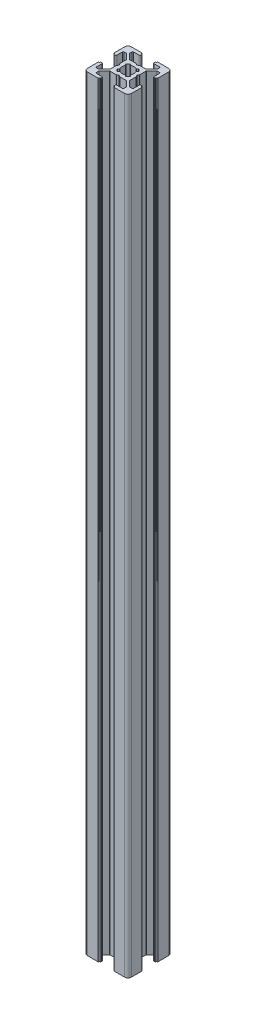
SolidWorks part; units mm, degrees
material "6061 Alloy"
ref_plane "Front Plane" through (0, 0, 0) normal (0, 0, 1) x (1, 0, 0)
ref_plane "Top Plane" through (0, 0, 0) normal (0, 1, 0) x (1, 0, 0)
ref_plane "Right Plane" through (0, 0, 0) normal (1, 0, 0) x (0, 0, -1)
sketch "Sketch2" plane through (0, 0, 0) normal (0, 1, 0) x (1, 0, 0)
  line L0 (-10, 3.75) -> (-10, 8.5)
  line L1 (10, -10) -> (-10, -10) construction
  line L2 (10, -10) -> (10, 10) construction
  line L3 (10, 10) -> (-10, 10) construction
  line L4 (-10, -10) -> (-10, 10) construction
  line L5 (10, -10) -> (-10, 10) construction
  line L6 (10, 10) -> (-10, -10) construction
  line L7 (-9.8, 3.55) -> (-9.7, 3.55)
  line L8 (-9.5, 3.35) -> (-9.5, 3.2)
  line L9 (-9.3, 3) -> (-8.9, 3)
  line L10 (-8.5, 3.4) -> (-8.5, 5.9)
  line L11 (-8.1, 6.3) -> (-7.1728, 6.3)
  line L12 (-6.8899, 6.1828) -> (-4.6172, 3.9101)
  line L13 (-4.5, 3.6272) -> (-4.5, 0.9196)
  line L14 (-4.4732, 0.8196) -> (-4.0577, 0.1)
  line L15 (-2.4797, 1.419) -> (-2.8968, 1.8361)
  line L16 (0, 0) -> (-10, 0) construction
  line L17 (-2.4797, -1.419) -> (-2.8968, -1.8361)
  line L18 (-4.4732, -0.8196) -> (-4.0577, -0.1)
  line L19 (-4.5, -3.6272) -> (-4.5, -0.9196)
  line L20 (-6.8899, -6.1828) -> (-4.6172, -3.9101)
  line L21 (-8.1, -6.3) -> (-7.1728, -6.3)
  line L22 (-8.5, -3.4) -> (-8.5, -5.9)
  line L23 (-9.3, -3) -> (-8.9, -3)
  line L24 (-9.5, -3.35) -> (-9.5, -3.2)
  line L25 (-9.8, -3.55) -> (-9.7, -3.55)
  line L26 (-10, -3.75) -> (-10, -8.5)
  line L27 (-6.3, 8.1) -> (-6.3, 7.1728)
  line L28 (1.419, 2.4797) -> (1.8361, 2.8968)
  line L29 (6.1828, 6.8899) -> (3.9101, 4.6172)
  line L30 (6.3, 8.1) -> (6.3, 7.1728)
  line L31 (3.75, 10) -> (8.5, 10)
  line L32 (3.55, 9.8) -> (3.55, 9.7)
  line L33 (3.35, 9.5) -> (3.2, 9.5)
  line L34 (3, 9.3) -> (3, 8.9)
  line L35 (3.4, 8.5) -> (5.9, 8.5)
  line L36 (3.6272, 4.5) -> (0.9196, 4.5)
  line L37 (0.8196, 4.4732) -> (0.1, 4.0577)
  line L38 (-0.8196, 4.4732) -> (-0.1, 4.0577)
  line L39 (-1.419, 2.4797) -> (-1.8361, 2.8968)
  line L40 (-3.6272, 4.5) -> (-0.9196, 4.5)
  line L41 (-6.1828, 6.8899) -> (-3.9101, 4.6172)
  line L42 (-3.4, 8.5) -> (-5.9, 8.5)
  line L43 (-3, 9.3) -> (-3, 8.9)
  line L44 (-3.35, 9.5) -> (-3.2, 9.5)
  line L45 (-3.55, 9.8) -> (-3.55, 9.7)
  line L46 (-3.75, 10) -> (-8.5, 10)
  line L47 (10, -3.75) -> (10, -8.5)
  line L48 (9.8, -3.55) -> (9.7, -3.55)
  line L49 (9.5, -3.35) -> (9.5, -3.2)
  line L50 (9.3, -3) -> (8.9, -3)
  line L51 (8.5, -3.4) -> (8.5, -5.9)
  line L52 (6.8899, -6.1828) -> (4.6172, -3.9101)
  line L53 (4.5, -3.6272) -> (4.5, -0.9196)
  line L54 (2.4797, -1.419) -> (2.8968, -1.8361)
  line L55 (4.4732, -0.8196) -> (4.0577, -0.1)
  line L56 (4.4732, 0.8196) -> (4.0577, 0.1)
  line L57 (4.5, 3.6272) -> (4.5, 0.9196)
  line L58 (8.5, 3.4) -> (8.5, 5.9)
  line L59 (9.3, 3) -> (8.9, 3)
  line L60 (9.5, 3.35) -> (9.5, 3.2)
  line L61 (9.8, 3.55) -> (9.7, 3.55)
  line L62 (10, 3.75) -> (10, 8.5)
  line L63 (8.1, 6.3) -> (7.1728, 6.3)
  line L64 (6.8899, 6.1828) -> (4.6172, 3.9101)
  line L65 (2.4797, 1.419) -> (2.8968, 1.8361)
  line L66 (8.1, -6.3) -> (7.1728, -6.3)
  line L67 (-3.75, -10) -> (-8.5, -10)
  line L68 (-3.55, -9.8) -> (-3.55, -9.7)
  line L69 (-3.35, -9.5) -> (-3.2, -9.5)
  line L70 (-3, -9.3) -> (-3, -8.9)
  line L71 (-3.4, -8.5) -> (-5.9, -8.5)
  line L72 (-6.3, -8.1) -> (-6.3, -7.1728)
  line L73 (-6.1828, -6.8899) -> (-3.9101, -4.6172)
  line L74 (-3.6272, -4.5) -> (-0.9196, -4.5)
  line L75 (-0.8196, -4.4732) -> (-0.1, -4.0577)
  line L76 (-1.419, -2.4797) -> (-1.8361, -2.8968)
  line L77 (1.419, -2.4797) -> (1.8361, -2.8968)
  line L78 (0.8196, -4.4732) -> (0.1, -4.0577)
  line L79 (3.6272, -4.5) -> (0.9196, -4.5)
  line L80 (6.1828, -6.8899) -> (3.9101, -4.6172)
  line L81 (6.3, -8.1) -> (6.3, -7.1728)
  line L82 (3.4, -8.5) -> (5.9, -8.5)
  line L83 (3, -9.3) -> (3, -8.9)
  line L84 (3.35, -9.5) -> (3.2, -9.5)
  line L85 (3.55, -9.8) -> (3.55, -9.7)
  line L86 (3.75, -10) -> (8.5, -10)
  arc A0 (-10, 8.5) -> (-8.5, 10) centre (-8.5, 8.5) cw
  arc A1 (-2.452, -1.2451) -> (-2.452, 1.2451) centre (0, 0) cw
  arc A2 (-2.9138, 2.0279) -> (-2.0279, 2.9138) centre (0, 0) cw
  arc A3 (-2.9138, -2.0279) -> (-2.0279, -2.9138) centre (0, 0) ccw
  arc A4 (-10, -8.5) -> (-8.5, -10) centre (-8.5, -8.5) ccw
  arc A5 (2.0279, 2.9138) -> (2.9138, 2.0279) centre (0, 0) cw
  arc A6 (8.5, 10) -> (10, 8.5) centre (8.5, 8.5) cw
  arc A7 (1.2451, 2.452) -> (-1.2451, 2.452) centre (0, 0) ccw
  arc A8 (2.452, 1.2451) -> (2.452, -1.2451) centre (0, 0) cw
  arc A9 (2.0279, -2.9138) -> (2.9138, -2.0279) centre (0, 0) ccw
  arc A10 (-1.2451, -2.452) -> (1.2451, -2.452) centre (0, 0) ccw
  arc A11 (8.5, -10) -> (10, -8.5) centre (8.5, -8.5) ccw
  arc A12 (-3.55, 9.8) -> (-3.75, 10) centre (-3.75, 9.8) ccw
  arc A13 (-3.35, 9.5) -> (-3.55, 9.7) centre (-3.35, 9.7) cw
  arc A14 (-3, 9.3) -> (-3.2, 9.5) centre (-3.2, 9.3) ccw
  arc A15 (3.75, 10) -> (3.55, 9.8) centre (3.75, 9.8) ccw
  arc A16 (3.2, 9.5) -> (3, 9.3) centre (3.2, 9.3) ccw
  arc A17 (3.55, 9.7) -> (3.35, 9.5) centre (3.35, 9.7) cw
  arc A18 (9.8, 3.55) -> (10, 3.75) centre (9.8, 3.75) ccw
  arc A19 (9.5, 3.35) -> (9.7, 3.55) centre (9.7, 3.35) cw
  arc A20 (9.3, 3) -> (9.5, 3.2) centre (9.3, 3.2) ccw
  arc A21 (9.5, -3.2) -> (9.3, -3) centre (9.3, -3.2) ccw
  arc A22 (9.7, -3.55) -> (9.5, -3.35) centre (9.7, -3.35) cw
  arc A23 (10, -3.75) -> (9.8, -3.55) centre (9.8, -3.75) ccw
  arc A24 (3.55, -9.8) -> (3.75, -10) centre (3.75, -9.8) ccw
  arc A25 (3.35, -9.5) -> (3.55, -9.7) centre (3.35, -9.7) cw
  arc A26 (3, -9.3) -> (3.2, -9.5) centre (3.2, -9.3) ccw
  arc A27 (-3.75, -10) -> (-3.55, -9.8) centre (-3.75, -9.8) ccw
  arc A28 (-3.55, -9.7) -> (-3.35, -9.5) centre (-3.35, -9.7) cw
  arc A29 (-3.2, -9.5) -> (-3, -9.3) centre (-3.2, -9.3) ccw
  arc A30 (4.4732, 0.8196) -> (4.5, 0.9196) centre (4.3, 0.9196) ccw
  arc A31 (4.0577, -0.1) -> (4.0577, 0.1) centre (4.2309, 0) cw
  arc A32 (4.5, -0.9196) -> (4.4732, -0.8196) centre (4.3, -0.9196) ccw
  arc A33 (0.8196, -4.4732) -> (0.9196, -4.5) centre (0.9196, -4.3) ccw
  arc A34 (-0.1, -4.0577) -> (0.1, -4.0577) centre (0, -4.2309) cw
  arc A35 (-0.9196, -4.5) -> (-0.8196, -4.4732) centre (-0.9196, -4.3) ccw
  arc A36 (-4.4732, -0.8196) -> (-4.5, -0.9196) centre (-4.3, -0.9196) ccw
  arc A37 (-4.0577, 0.1) -> (-4.0577, -0.1) centre (-4.2309, 0) cw
  arc A38 (-4.5, 0.9196) -> (-4.4732, 0.8196) centre (-4.3, 0.9196) ccw
  arc A39 (0.9196, 4.5) -> (0.8196, 4.4732) centre (0.9196, 4.3) ccw
  arc A40 (0.1, 4.0577) -> (-0.1, 4.0577) centre (0, 4.2309) cw
  arc A41 (-0.8196, 4.4732) -> (-0.9196, 4.5) centre (-0.9196, 4.3) ccw
  arc A42 (-9.8, -3.55) -> (-10, -3.75) centre (-9.8, -3.75) ccw
  arc A43 (-9.5, -3.35) -> (-9.7, -3.55) centre (-9.7, -3.35) cw
  arc A44 (-9.3, -3) -> (-9.5, -3.2) centre (-9.3, -3.2) ccw
  arc A45 (-9.5, 3.2) -> (-9.3, 3) centre (-9.3, 3.2) ccw
  arc A46 (-9.7, 3.55) -> (-9.5, 3.35) centre (-9.7, 3.35) cw
  arc A47 (-10, 3.75) -> (-9.8, 3.55) centre (-9.8, 3.75) ccw
  arc A48 (-8.9, 3) -> (-8.5, 3.4) centre (-8.9, 3.4) ccw
  arc A49 (-8.5, 5.9) -> (-8.1, 6.3) centre (-8.1, 5.9) cw
  arc A50 (-3.4, 8.5) -> (-3, 8.9) centre (-3.4, 8.9) ccw
  arc A51 (-6.3, 8.1) -> (-5.9, 8.5) centre (-5.9, 8.1) cw
  arc A52 (-6.3, 7.1728) -> (-6.1828, 6.8899) centre (-5.9, 7.1728) ccw
  arc A53 (-7.1728, 6.3) -> (-6.8899, 6.1828) centre (-7.1728, 5.9) cw
  arc A54 (-4.6172, 3.9101) -> (-4.5, 3.6272) centre (-4.9, 3.6272) cw
  arc A55 (-3.6272, 4.5) -> (-3.9101, 4.6172) centre (-3.6272, 4.9) cw
  arc A56 (8.5, 3.4) -> (8.9, 3) centre (8.9, 3.4) ccw
  arc A57 (8.5, 5.9) -> (8.1, 6.3) centre (8.1, 5.9) ccw
  arc A58 (7.1728, 6.3) -> (6.8899, 6.1828) centre (7.1728, 5.9) ccw
  arc A59 (3, 8.9) -> (3.4, 8.5) centre (3.4, 8.9) ccw
  arc A60 (6.3, 8.1) -> (5.9, 8.5) centre (5.9, 8.1) ccw
  arc A61 (6.1828, 6.8899) -> (6.3, 7.1728) centre (5.9, 7.1728) ccw
  arc A62 (3.9101, 4.6172) -> (3.6272, 4.5) centre (3.6272, 4.9) cw
  arc A63 (4.5, 3.6272) -> (4.6172, 3.9101) centre (4.9, 3.6272) cw
  arc A64 (8.9, -3) -> (8.5, -3.4) centre (8.9, -3.4) ccw
  arc A65 (8.5, -5.9) -> (8.1, -6.3) centre (8.1, -5.9) cw
  arc A66 (6.8899, -6.1828) -> (7.1728, -6.3) centre (7.1728, -5.9) ccw
  arc A67 (4.6172, -3.9101) -> (4.5, -3.6272) centre (4.9, -3.6272) cw
  arc A68 (3.6272, -4.5) -> (3.9101, -4.6172) centre (3.6272, -4.9) cw
  arc A69 (6.1828, -6.8899) -> (6.3, -7.1728) centre (5.9, -7.1728) cw
  arc A70 (6.3, -8.1) -> (5.9, -8.5) centre (5.9, -8.1) cw
  arc A71 (3.4, -8.5) -> (3, -8.9) centre (3.4, -8.9) ccw
  arc A72 (-3, -8.9) -> (-3.4, -8.5) centre (-3.4, -8.9) ccw
  arc A73 (-5.9, -8.5) -> (-6.3, -8.1) centre (-5.9, -8.1) cw
  arc A74 (-6.3, -7.1728) -> (-6.1828, -6.8899) centre (-5.9, -7.1728) cw
  arc A75 (-3.9101, -4.6172) -> (-3.6272, -4.5) centre (-3.6272, -4.9) cw
  arc A76 (-4.5, -3.6272) -> (-4.6172, -3.9101) centre (-4.9, -3.6272) cw
  arc A77 (-6.8899, -6.1828) -> (-7.1728, -6.3) centre (-7.1728, -5.9) cw
  arc A78 (-8.1, -6.3) -> (-8.5, -5.9) centre (-8.1, -5.9) cw
  arc A79 (-8.5, -3.4) -> (-8.9, -3) centre (-8.9, -3.4) ccw
  arc A80 (-2.4797, -1.419) -> (-2.452, -1.2451) centre (-2.5858, -1.313) ccw
  arc A81 (-2.9138, -2.0279) -> (-2.8968, -1.8361) centre (-2.7907, -1.9422) cw
  arc A82 (-1.8361, -2.8968) -> (-2.0279, -2.9138) centre (-1.9422, -2.7907) cw
  arc A83 (-1.2451, -2.452) -> (-1.419, -2.4797) centre (-1.313, -2.5858) ccw
  arc A84 (1.2451, -2.452) -> (1.419, -2.4797) centre (1.313, -2.5858) cw
  arc A85 (2.0279, -2.9138) -> (1.8361, -2.8968) centre (1.9422, -2.7907) cw
  arc A86 (2.9138, -2.0279) -> (2.8968, -1.8361) centre (2.7907, -1.9422) ccw
  arc A87 (2.452, -1.2451) -> (2.4797, -1.419) centre (2.5858, -1.313) ccw
  arc A88 (2.452, 1.2451) -> (2.4797, 1.419) centre (2.5858, 1.313) cw
  arc A89 (2.8968, 1.8361) -> (2.9138, 2.0279) centre (2.7907, 1.9422) ccw
  arc A90 (2.0279, 2.9138) -> (1.8361, 2.8968) centre (1.9422, 2.7907) ccw
  arc A91 (1.419, 2.4797) -> (1.2451, 2.452) centre (1.313, 2.5858) cw
  arc A92 (-1.2451, 2.452) -> (-1.419, 2.4797) centre (-1.313, 2.5858) cw
  arc A93 (-1.8361, 2.8968) -> (-2.0279, 2.9138) centre (-1.9422, 2.7907) ccw
  arc A94 (-2.8968, 1.8361) -> (-2.9138, 2.0279) centre (-2.7907, 1.9422) cw
  arc A95 (-2.452, 1.2451) -> (-2.4797, 1.419) centre (-2.5858, 1.313) ccw
  point P0 (0, 0)
  point P119 (-3.55, 10)
  point P122 (-3.55, 9.5)
  point P125 (-3, 9.5)
  point P128 (3.55, 10)
  point P131 (3, 9.5)
  point P134 (3.55, 9.5)
  point P137 (10, 3.55)
  point P140 (9.5, 3.55)
  point P143 (9.5, 3)
  point P146 (9.5, -3)
  point P149 (9.5, -3.55)
  point P152 (10, -3.55)
  point P155 (3.55, -10)
  point P158 (3.55, -9.5)
  point P161 (3, -9.5)
  point P164 (-3.55, -10)
  point P167 (-3.55, -9.5)
  point P170 (-3, -9.5)
  point P173 (4.5, 0.866)
  point P176 (4, 0)
  point P179 (4.5, -0.866)
  point P182 (0.866, -4.5)
  point P185 (0, -4)
  point P188 (-0.866, -4.5)
  point P191 (-4.5, -0.866)
  point P194 (-4, 0)
  point P197 (-4.5, 0.866)
  point P200 (0.866, 4.5)
  point P203 (0, 4)
  point P206 (-0.866, 4.5)
  point P209 (-10, -3.55)
  point P212 (-9.5, -3.55)
  point P215 (-9.5, -3)
  point P218 (-9.5, 3)
  point P221 (-9.5, 3.55)
  point P224 (-10, 3.55)
  point P227 (-8.5, 3)
  point P230 (-8.5, 6.3)
  point P233 (-3, 8.5)
  point P236 (-6.3, 8.5)
  point P239 (-6.3, 7.0071)
  point P242 (-7.0071, 6.3)
  point P245 (-4.5, 3.7929)
  point P248 (-3.7929, 4.5)
  point P251 (8.5, 3)
  point P254 (8.5, 6.3)
  point P257 (7.0071, 6.3)
  point P260 (3, 8.5)
  point P263 (6.3, 8.5)
  point P266 (6.3, 7.0071)
  point P269 (3.7929, 4.5)
  point P272 (4.5, 3.7929)
  point P275 (8.5, -3)
  point P278 (8.5, -6.3)
  point P281 (7.0071, -6.3)
  point P284 (4.5, -3.7929)
  point P287 (3.7929, -4.5)
  point P290 (6.3, -7.0071)
  point P293 (6.3, -8.5)
  point P296 (3, -8.5)
  point P299 (-3, -8.5)
  point P302 (-6.3, -8.5)
  point P305 (-6.3, -7.0071)
  point P308 (-3.7929, -4.5)
  point P311 (-4.5, -3.7929)
  point P314 (-7.0071, -6.3)
  point P317 (-8.5, -6.3)
  point P320 (-8.5, -3)
  point P323 (-2.4012, -1.3405)
  point P326 (-2.9839, -1.9232)
  point P329 (-1.9232, -2.9839)
  point P332 (-1.3405, -2.4012)
  point P335 (1.3405, -2.4012)
  point P338 (1.9232, -2.9839)
  point P341 (2.9839, -1.9232)
  point P344 (2.4012, -1.3405)
  point P347 (2.4012, 1.3405)
  point P350 (2.9839, 1.9232)
  point P353 (1.9232, 2.9839)
  point P356 (1.3405, 2.4012)
  point P359 (-1.3405, 2.4012)
  point P362 (-1.9232, 2.9839)
  point P365 (-2.9839, 1.9232)
  point P368 (-2.4012, 1.3405)
  dimension "D3" = 1.5
  dimension "D10" = 2.75
  dimension "D11" = 3.55
  dimension "D16" = 0.2
  dimension "D17" = 0.4
  dimension "D18" = 0.15
  dimension "D1" = 20
  dimension "D2" = 20
  dimension "D4" = 6.45
  dimension "D5" = 0.5
  dimension "D6" = 1
  dimension "D7" = 7
  dimension "D8" = 4
  dimension "D9" = 1
  dimension "D12" = 1.5
  dimension "D13" = 3.3
  dimension "D14" = 4
  dimension "D15" = 60
extrude "Boss-Extrude1" add sketch "Sketch2" along normal mid plane 350 contours A95 A1 A80 L17 A81 A3 A82 L76 A83 A10 A84 L77 A85 A9 A86 L54 A87 A8 A88 L65 A89 A5 A90 L28 A91 A7 A92 L39 A93 A2 A94 L15 | L10 A49 L11 A53 L12 A54 L13 A38 L14 A37 L18 A36 L19 A76 L20 A77 L21 A78 L22 A79 L23 A44 L24 A43 L25 A42 L26 A4 L67 A27 L68 A28 L69 A29 L70 A72 L71 A73 L72 A74 L73 A75 L74 A35 L75 A34 L78 A33 L79 A68 L80 A69 L81 A70 L82 A71 L83 A26 L84 A25 L85 A24 L86 A11 L47 A23 L48 A22 L49 A21 L50 A64 L51 A65 L66 A66 L52 A67 L53 A32 L55 A31 L56 A30 L57 A63 L64 A58 L63 A57 L58 A56 L59 A20 L60 A19 L61 A18 L62 A6 L31 A15 L32 A17 L33 A16 L34 A59 L35 A60 L30 A61 L29 A62 L36 A39 L37 A40 L38 A41 L40 A55 L41 A52 L27 A51 L42 A50 L43 A14 L44 A13 L45 A12 L46 A0 L0 A47 L7 A46 L8 A45 L9 A48
